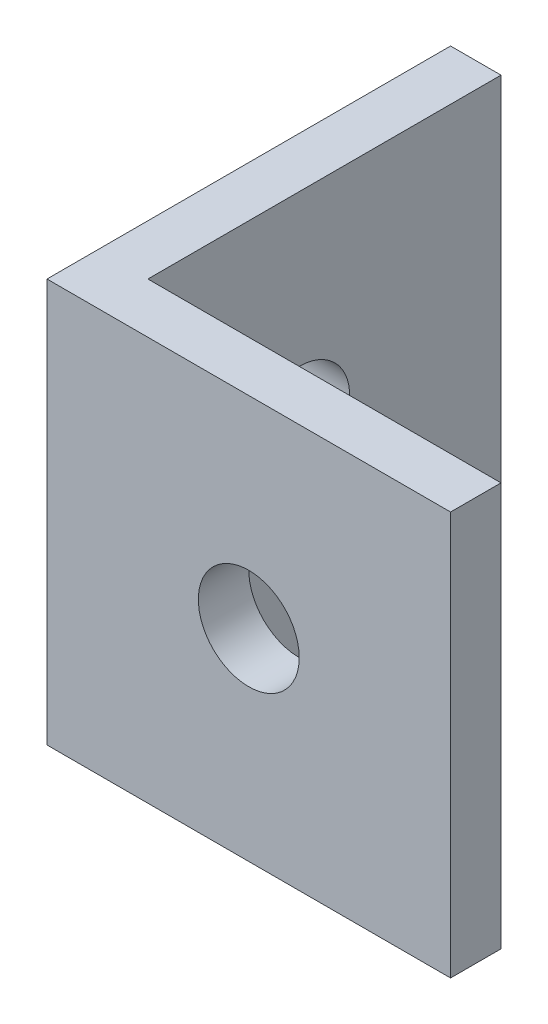
SolidWorks part; units mm, degrees
ref_plane "Front Plane" through (0, 0, 0) normal (0, 0, 1) x (1, 0, 0)
ref_plane "Top Plane" through (0, 0, 0) normal (0, 1, 0) x (1, 0, 0)
ref_plane "Right Plane" through (0, 0, 0) normal (1, 0, 0) x (0, 0, -1)
sketch "Sketch1" plane through (0, 0, 0) normal (0, 1, 0) x (1, 0, 0)
  line L0 (0, 0) -> (25.4, 0)
  line L1 (25.4, 0) -> (25.4, 3.175)
  line L2 (25.4, 3.175) -> (3.175, 3.175)
  line L3 (3.175, 3.175) -> (3.175, 25.4)
  line L4 (3.175, 25.4) -> (0, 25.4)
  line L5 (0, 25.4) -> (0, 0)
  dimension "D1" = 3.175
  dimension "D2" = 25.4
extrude "Boss-Extrude1" add sketch "Sketch1" along normal blind 25.4
sketch "Sketch3" plane through (0, 0, 0) normal (0, 0, 1) x (1, 0, 0)
  line L0 (12.7, 25.4) -> (12.7, 0) construction
  line L1 (0, 25.4) -> (25.4, 25.4) construction
  line L2 (0, 0) -> (25.4, 0) construction
  line L3 (25.4, 12.7) -> (0, 12.7) construction
  line L4 (25.4, 25.4) -> (25.4, 0) construction
  line L5 (0, 25.4) -> (0, 0) construction
  circle A0 centre (12.7, 12.7) radius 3.175
  dimension "D1" = 6.35
extrude "Cut-Extrude2" cut sketch "Sketch3" against normal through all
sketch "Sketch4" plane through (0, 0, 0) normal (-1, 0, 0) x (0, 0, 1)
  line L0 (-12.7, 25.4) -> (-12.7, 0) construction
  line L1 (-25.4, 25.4) -> (0, 25.4) construction
  line L2 (-25.4, 0) -> (0, 0) construction
  line L3 (0, 12.7) -> (-25.4, 12.7) construction
  line L4 (0, 25.4) -> (0, 0) construction
  line L5 (-25.4, 25.4) -> (-25.4, 0) construction
  circle A0 centre (-12.7, 12.7) radius 3.175
  dimension "D1" = 6.35
extrude "Cut-Extrude3" cut sketch "Sketch4" against normal through all
